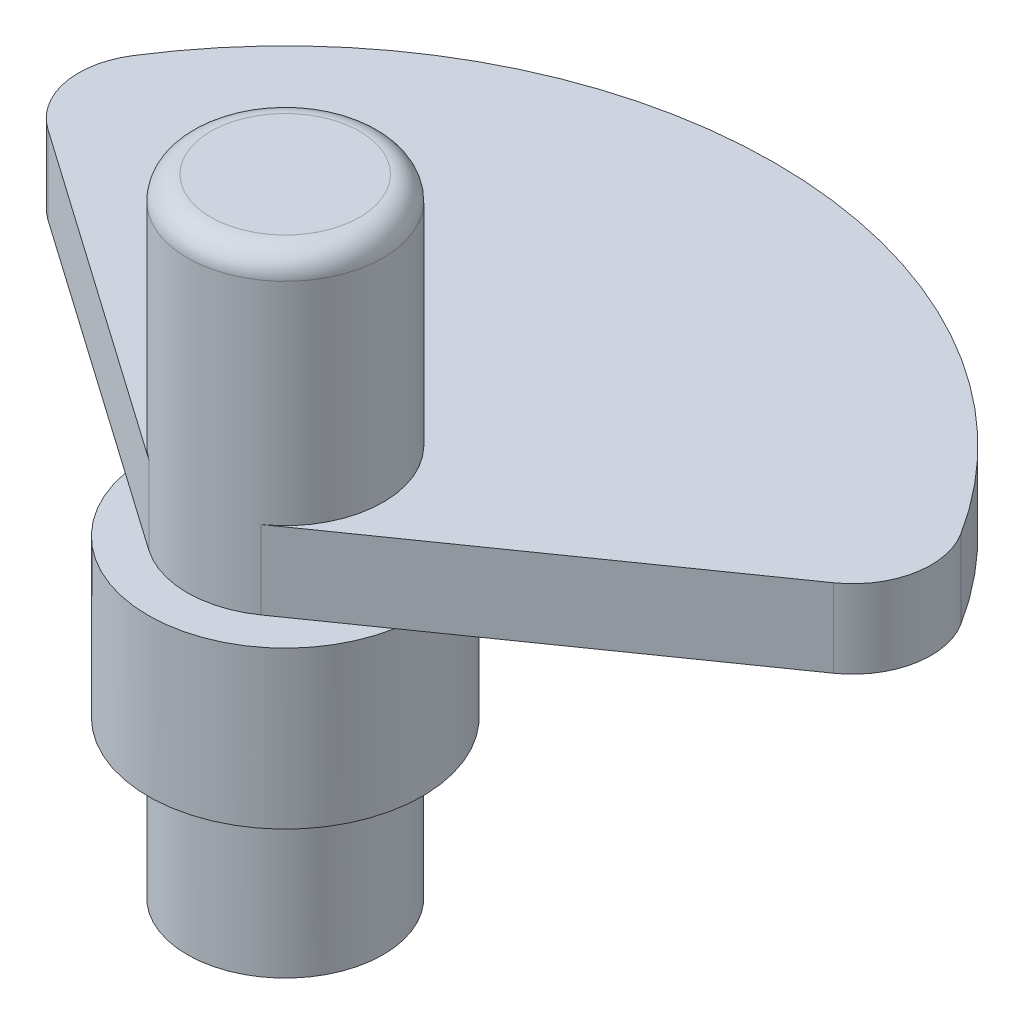
SolidWorks part; units mm, degrees
ref_plane "Front Plane" through (0, 0, 0) normal (0, 0, 1) x (1, 0, 0)
ref_plane "Top Plane" through (0, 0, 0) normal (0, 1, 0) x (1, 0, 0)
ref_plane "Right Plane" through (0, 0, 0) normal (1, 0, 0) x (0, 0, -1)
sketch "Sketch1" plane through (0, 0, 0) normal (0, 1, 0) x (1, 0, 0)
  line L0 (0, 0) -> (-39049.5542, 0) construction
  line L1 (0, 0) -> (0, -39049.5542) construction
  line L2 (-50.1264, 19.8392) -> (-7.1697, -10.2394)
  line L3 (50.1264, 19.8392) -> (7.1697, -10.2394)
  arc A0 (-7.1697, -10.2394) -> (7.1697, -10.2394) centre (0, 0) ccw
  arc A1 (52.846, 33.3699) -> (-52.846, 33.3699) centre (0, 0) ccw
  arc A2 (50.1264, 19.8392) -> (52.846, 33.3699) centre (44.3906, 28.0307) ccw
  arc A3 (-50.1264, 19.8392) -> (-52.846, 33.3699) centre (-44.3906, 28.0307) cw
  point P13 (57.3323, 24.8848)
  point P16 (-57.3323, 24.8848)
  dimension "D1" = 25
  dimension "D2" = 125
  dimension "D3" = 0
  dimension "D5" = 10
  dimension "D4" = 35
extrude "Boss-Extrude1" add sketch "Sketch1" along normal blind 10 contours L2 A0 L3 A2 A1 A3
sketch "Sketch2" plane through (0, 10, 0) normal (0, 1, 0) x (1, 0, 0)
  line L0 (0, 0) -> (-50000, 0) construction
  line L1 (0, 0) -> (0, -50000) construction
  circle A0 centre (0, 0) radius 12.5
extrude "Boss-Extrude2" add sketch "Sketch2" along normal blind 30 and the other way blind 50
sketch "Sketch3" plane through (0, 0, 0) normal (0, -1, 0) x (1, 0, 0)
  line L0 (0, 0) -> (-50000, 0) construction
  line L1 (0, 0) -> (0, -50000) construction
  circle A0 centre (0, 0) radius 17.5
  dimension "D1" = 35
extrude "Boss-Extrude3" add sketch "Sketch3" along normal blind 20
fillet "Fillet1" radius 3 1 edges at (0, 40, 12.5)
sketch "Sketch4" plane through (0, -40, 0) normal (0, -1, 0) x (1, 0, 0)
  line L0 (0, 0) -> (-50000, 0) construction
  line L1 (0, 0) -> (0, -50000) construction
  circle A0 centre (0, 0) radius 9 construction
  circle A1 centre (0, 9) radius 1.5
  circle A2 centre (9, 0) radius 1.5
  circle A3 centre (0, -9) radius 1.5
  circle A4 centre (-9, 0) radius 1.5
  point P19 (0, 0)
  dimension "D1" = 18
  dimension "D2" = 3
  dimension "D3" = 4
extrude "Cut-Extrude1" cut sketch "Sketch4" against normal blind 10
